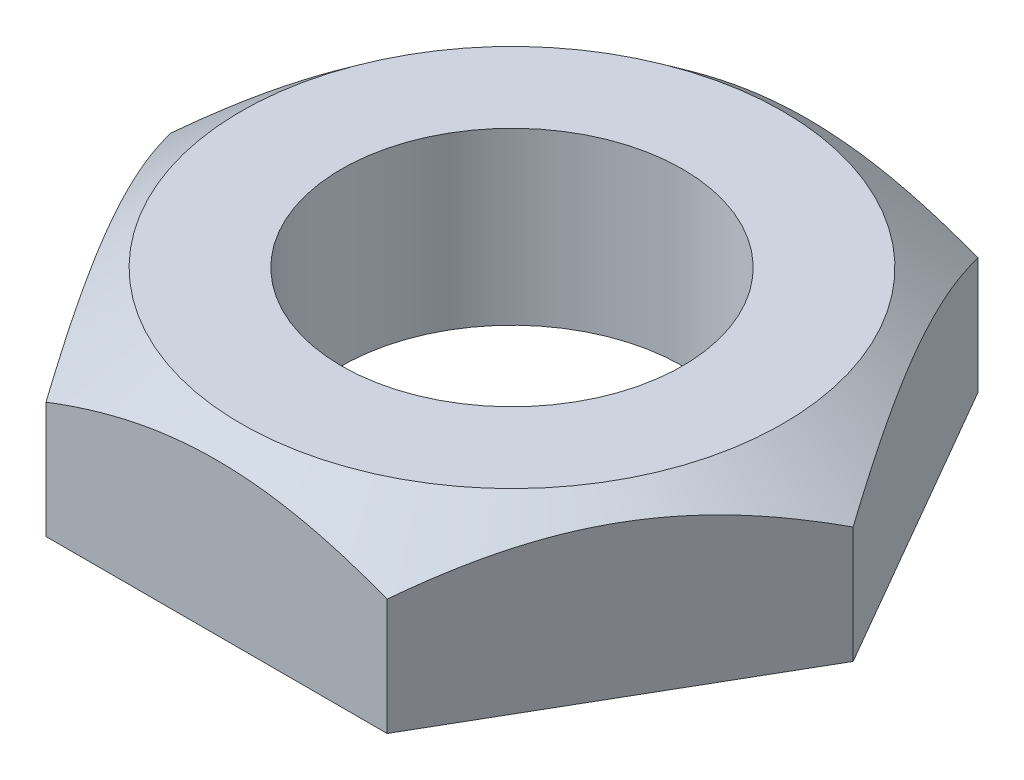
SolidWorks part; units mm, degrees
material "1023 Carbon Steel Sheet (SS)"
ref_plane "Front Plane" through (0, 0, 0) normal (0, 0, 1) x (1, 0, 0)
ref_plane "Top Plane" through (0, 0, 0) normal (0, 1, 0) x (1, 0, 0)
ref_plane "Right Plane" through (0, 0, 0) normal (1, 0, 0) x (0, 0, -1)
sketch "Sketch1" plane through (0, 0, 0) normal (0, 1, 0) x (1, 0, 0)
  line L1 (30, 0) -> (15, 25.9808)
  line L2 (15, 25.9808) -> (-15, 25.9808)
  line L3 (-15, 25.9808) -> (-30, 0)
  line L4 (-30, 0) -> (-15, -25.9808)
  line L5 (-15, -25.9808) -> (15, -25.9808)
  line L6 (15, -25.9808) -> (30, 0)
  circle A0 centre (0, 0) radius 25.9808 construction
  circle A1 centre (0, 0) radius 15
  dimension "D1" = 30
  dimension "D2" = 60
extrude "Boss-Extrude1" add sketch "Sketch1" along normal blind 15
cosmetic thread "Cosmetic Thread1" parameters "D2"=31
sketch "Sketch3" plane through (0, 0, 0) normal (0, 0, 1) x (1, 0, 0)
  line L0 (-30, 15) -> (-30, 10.2359)
  line L1 (-30, 15) -> (-30, 0) construction
  line L2 (-30, 10.2359) -> (-23.8137, 15)
  line L3 (-30, 15) -> (-15, 15) construction
  line L4 (-23.8137, 15) -> (-30, 15)
  line L5 (0, 0) -> (0, 23.1832) construction
revolve "Cut-Revolve1" cut sketch "Sketch3" angle 360 about L5
